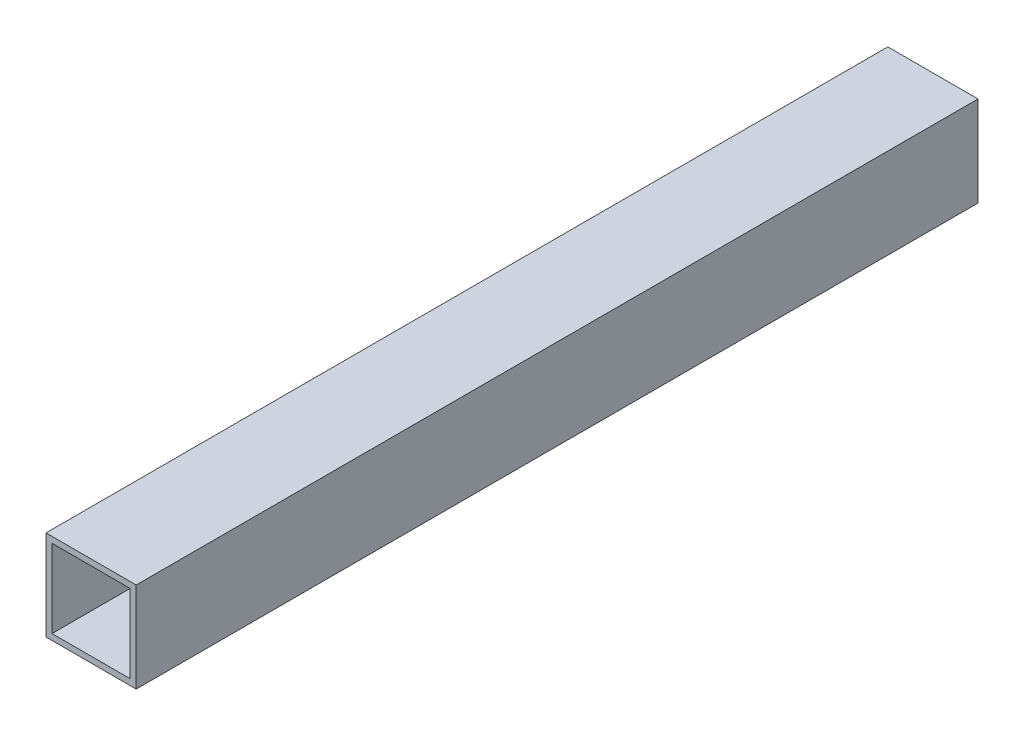
SolidWorks part; units mm, degrees
material "Hexcel AS4C (3000 Filaments)"
ref_plane "Front Plane" through (0, 0, 0) normal (0, 0, 1) x (1, 0, 0)
ref_plane "Top Plane" through (0, 0, 0) normal (0, 1, 0) x (1, 0, 0)
ref_plane "Right Plane" through (0, 0, 0) normal (1, 0, 0) x (0, 0, -1)
sketch "Sketch1" plane through (0, 0, 0) normal (0, 0, 1) x (1, 0, 0)
  line L0 (-6.5, 6.5) -> (6.5, 6.5)
  line L1 (-7.5, -7.5) -> (7.5, -7.5)
  line L2 (-7.5, -7.5) -> (-7.5, 7.5)
  line L3 (-7.5, 7.5) -> (7.5, 7.5)
  line L4 (7.5, -7.5) -> (7.5, 7.5)
  line L5 (-7.5, -7.5) -> (7.5, 7.5) construction
  line L6 (-7.5, 7.5) -> (7.5, -7.5) construction
  line L7 (6.5, -6.5) -> (6.5, 6.5)
  line L8 (-6.5, -6.5) -> (6.5, -6.5)
  line L9 (-6.5, -6.5) -> (-6.5, 6.5)
  point P0 (0, 0)
  dimension "D1" = 15
  dimension "D2" = 15
  dimension "D3" = 1
extrude "Boss-Extrude1" add sketch "Sketch1" along normal blind 140
